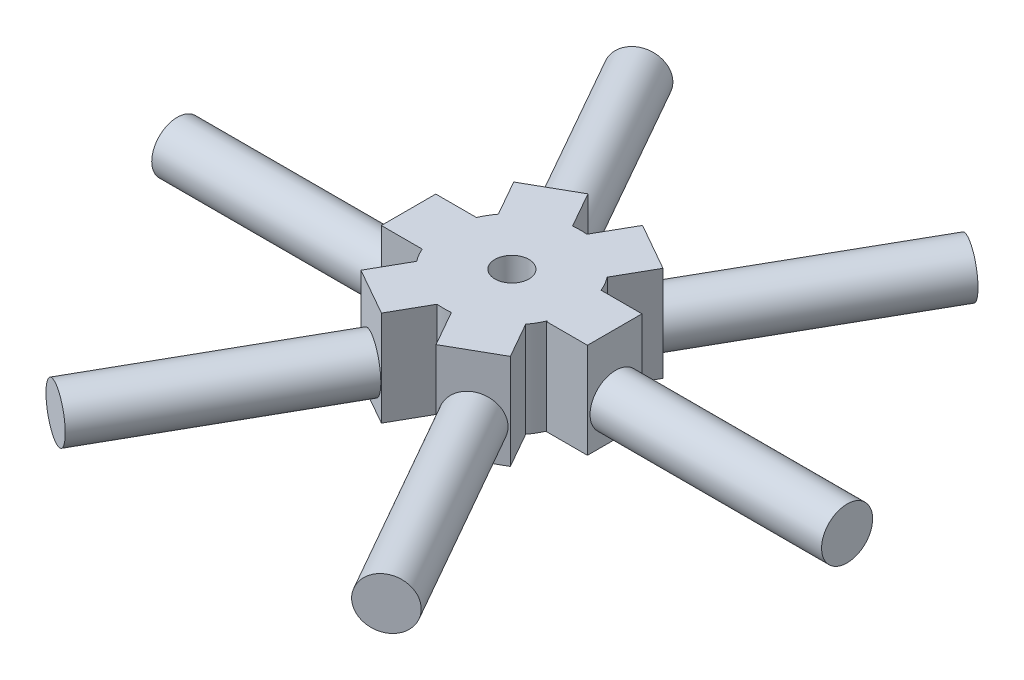
SolidWorks part; units mm, degrees
ref_plane "Front Plane" through (0, 0, 0) normal (0, 0, 1) x (1, 0, 0)
ref_plane "Top Plane" through (0, 0, 0) normal (0, 1, 0) x (1, 0, 0)
ref_plane "Right Plane" through (0, 0, 0) normal (1, 0, 0) x (0, 0, -1)
sketch "Sketch1" plane through (0, 0, 0) normal (0, 1, 0) x (1, 0, 0)
  circle A0 centre (0, 0) radius 3.175
  circle A1 centre (0, 0) radius 12.7
  dimension "D1" = 6.35
  dimension "D2" = 25.4
extrude "Boss-Extrude1" add sketch "Sketch1" along normal blind 22.86
ref_plane "Plane1" through (0, 11.43, 0) normal (0, -1, 0) x (-1, 0, 0)
sketch3d "3DSketch2"
  circle A0 centre (0, 0, 0) radius 12.7 construction
  circle A1 centre (0, 0, 0) radius 12.7
  point P2 (0, 12.7, 0)
  point P4 (0, 12.7, 0)
sketch "Sketch2" plane through (0, 11.43, 0) normal (0, -1, 0) x (-1, 0, 0)
  circle A0 centre (0, 0) radius 12.7 construction
  circle A1 centre (0, 0) radius 12.7
  circle A2 centre (0, 0) radius 12.7 construction
  circle A3 centre (0, 0) radius 12.7
  circle A4 centre (0, 0) radius 12.7
  point P7 (-12.7, 0)
sketch "Sketch3" plane through (0, 0, 0) normal (0, 0, 1) x (1, 0, 0)
  line L0 (12.7, 22.86) -> (-12.7, 22.86) construction
  point P0 (0, 22.86)
  point P1 (0, 0)
ref_plane "Plane2" through (0, 0, 0) normal (0, 1, 0) x (1, 0, 0)
sketch "Sketch4" plane through (0, 0, 0) normal (0, 1, 0) x (1, 0, 0)
  line L0 (-11.6219, 5.0393) -> (11.7103, 4.9153) construction
  line L2 (-11.6219, -5.1207) -> (11.7103, -5.2447) construction
  line L3 (-10.16, 7.62) -> (1.3382, -12.6293) construction
  line L6 (1.3382, -12.6293) -> (-1.3217, 12.631) construction
  line L15 (11.7103, -5.2447) -> (11.7103, 4.9153)
  line L16 (11.7103, 4.9153) -> (19.3303, 4.9153)
  line L17 (19.3303, 4.9153) -> (19.3303, -5.2447)
  line L18 (19.3303, -5.2447) -> (11.7103, -5.2447)
  line L24 (-11.6219, 5.0393) -> (-11.6219, -5.1207)
  line L28 (-11.6219, -5.1207) -> (-19.2419, -5.1207)
  line L29 (-19.2419, -5.1207) -> (-19.2419, 5.0393)
  line L30 (-19.2419, 5.0393) -> (-11.6219, 5.0393)
  line L36 (-10.16, 7.62) -> (-1.3217, 12.631)
  line L37 (-10.16, 7.62) -> (-13.9183, 14.2487)
  line L38 (-13.9183, 14.2487) -> (-5.08, 19.2597)
  line L39 (-5.08, 19.2597) -> (-1.3217, 12.631)
  line L40 (-1.3217, 12.631) -> (10.1699, -7.6068) construction
  line L41 (1.3382, 12.6293) -> (10.1699, 7.6068)
  line L42 (10.1699, 7.6068) -> (13.9368, 14.2306)
  line L43 (13.9368, 14.2306) -> (5.1051, 19.2531)
  line L44 (5.1051, 19.2531) -> (1.3382, 12.6293)
  line L45 (10.1699, -7.6068) -> (10.1699, 7.6068) construction
  line L46 (-10.16, -7.62) -> (-1.3217, -12.631)
  line L47 (-1.3217, -12.631) -> (-5.08, -19.2597)
  line L48 (-5.08, -19.2597) -> (-13.9183, -14.2487)
  line L49 (-13.9183, -14.2487) -> (-10.16, -7.62)
  line L50 (-10.16, -7.62) -> (-13.9183, -14.2487)
  line L51 (10.1699, 7.6068) -> (-1.3382, -12.6293) construction
  line L52 (1.3382, -12.6293) -> (10.1699, -7.6068)
  line L53 (10.1699, -7.6068) -> (13.9368, -14.2306)
  line L54 (13.9368, -14.2306) -> (5.1051, -19.2531)
  line L55 (5.1051, -19.2531) -> (1.3382, -12.6293)
  line L56 (10.1699, 7.6068) -> (10.123, 7.6691)
  line L57 (1.3382, 12.6293) -> (-10.16, -7.62) construction
  circle A0 centre (0, 0) radius 12.7 construction
  circle A1 centre (0, 0) radius 12.7 construction
  dimension "D2" = 7.62
  dimension "D3" = 10.16
  dimension "D4" = 7.62
  dimension "D5" = 10.16
  dimension "D6" = 7.62
  dimension "D7" = 7.62
  dimension "D8" = 10.16
  dimension "D9" = 7.62
  dimension "D10" = 7.62
  dimension "D11" = 10.16
  dimension "D12" = 10.16
  dimension "D13" = 10.16
extrude "Boss-Extrude2" add sketch "Sketch4" along normal blind 22.86
ref_plane "Plane3" through (21.8703, 0, 0) normal (1, 0, 0) x (0, 0, -1)
sketch "Sketch5" plane through (21.8703, 0, 0) normal (1, 0, 0) x (0, 0, -1)
  line L0 (0, 26.8622) -> (0, -1.3028) construction
  line L1 (-8.4495, 11.43) -> (4.9153, 11.43) construction
  line L2 (-12.7, 11.43) -> (12.7, 11.43) construction
  line L3 (4.9153, 22.86) -> (4.9153, 0) construction
  point P9 (0, 11.43)
ref_plane "Plane4" through (-21.7819, 0, 0) normal (-1, 0, 0) x (0, 0, 1)
sketch "Sketch8" plane through (-21.7819, 0, 0) normal (-1, 0, 0) x (0, 0, 1)
  circle A0 centre (0, 11.43) radius 3
extrude "Cut-Extrude1" cut sketch "Sketch8" against normal through all both and the other way through all
ref_plane "Plane5" through (10.7766, 0, -18.9498) normal (0.4943, 0, -0.8693) x (-0.8693, 0, -0.4943)
sketch "Sketch9" plane through (10.7766, 0, -18.9498) normal (0.4943, 0, -0.8693) x (-0.8693, 0, -0.4943)
  line L0 (-12.7, 11.43) -> (12.7, 11.43) construction
  circle A0 centre (0, 11.43) radius 3
extrude "Cut-Extrude2" cut sketch "Sketch9" against normal through all both
ref_plane "Plane6" through (10.7766, 0, 18.9498) normal (0.4943, 0, 0.8693) x (0.8693, 0, -0.4943)
sketch "Sketch10" plane through (10.7766, 0, 18.9498) normal (0.4943, 0, 0.8693) x (0.8693, 0, -0.4943)
  line L0 (-12.7, 11.43) -> (12.7, 11.43) construction
  circle A0 centre (0, 11.43) radius 3
extrude "Cut-Extrude3" cut sketch "Sketch10" against normal through all both
sketch "Sketch12" plane through (0, 0, 0) normal (0, 1, 0) x (1, 0, 0)
  circle A0 centre (0, 0) radius 23.4016
extrude "Cut-Extrude4" cut sketch "Sketch12" along normal blind 5.08
sketch "Sketch14" plane through (21.8703, 0, 0) normal (1, 0, 0) x (0, 0, -1)
  circle A0 centre (0, 11.43) radius 4.7625
extrude "Boss-Extrude3" add sketch "Sketch14" along normal blind 40.64 and the other way blind 2.54
sketch "Sketch15" plane through (10.7766, 0, 18.9498) normal (0.4943, 0, 0.8693) x (0.8693, 0, -0.4943)
  line L0 (-12.7, 11.43) -> (12.7, 11.43) construction
  circle A0 centre (0, 11.43) radius 4.7625
extrude "Boss-Extrude4" add sketch "Sketch15" along normal blind 40.64 and the other way blind 2.54
sketch "Sketch16" plane through (-21.7819, 0, 0) normal (-1, 0, 0) x (0, 0, 1)
  circle A0 centre (0, 11.43) radius 4.7625
extrude "Boss-Extrude5" add sketch "Sketch16" along normal blind 40.64 and the other way blind 2.54
sketch "Sketch17" plane through (10.7766, 0, -18.9498) normal (0.4943, 0, -0.8693) x (-0.8693, 0, -0.4943)
  line L0 (-12.7, 11.43) -> (12.7, 11.43) construction
  circle A0 centre (0, 11.43) radius 4.7625
extrude "Boss-Extrude6" add sketch "Sketch17" along normal blind 40.64 and the other way blind 2.54
ref_plane "Plane7" through (-9.4991, 0, -16.7542) normal (-0.4932, 0, -0.8699) x (-0.8699, 0, 0.4932)
sketch "Sketch18" plane through (-9.4991, 0, -16.7542) normal (-0.4932, 0, -0.8699) x (-0.8699, 0, 0.4932)
  line L0 (-12.7, 11.43) -> (12.7, 11.43) construction
  circle A0 centre (0, 11.43) radius 4.7625
extrude "Boss-Extrude7" add sketch "Sketch18" along normal blind 43.18
ref_plane "Plane8" through (-9.4991, 0, 16.7542) normal (-0.4932, 0, 0.8699) x (0.8699, 0, 0.4932)
sketch "Sketch19" plane through (-9.4991, 0, 16.7542) normal (-0.4932, 0, 0.8699) x (0.8699, 0, 0.4932)
  line L0 (-12.7, 11.43) -> (12.7, 11.43) construction
  circle A0 centre (0, 11.43) radius 4.7625
extrude "Boss-Extrude8" add sketch "Sketch19" along normal blind 43.18
